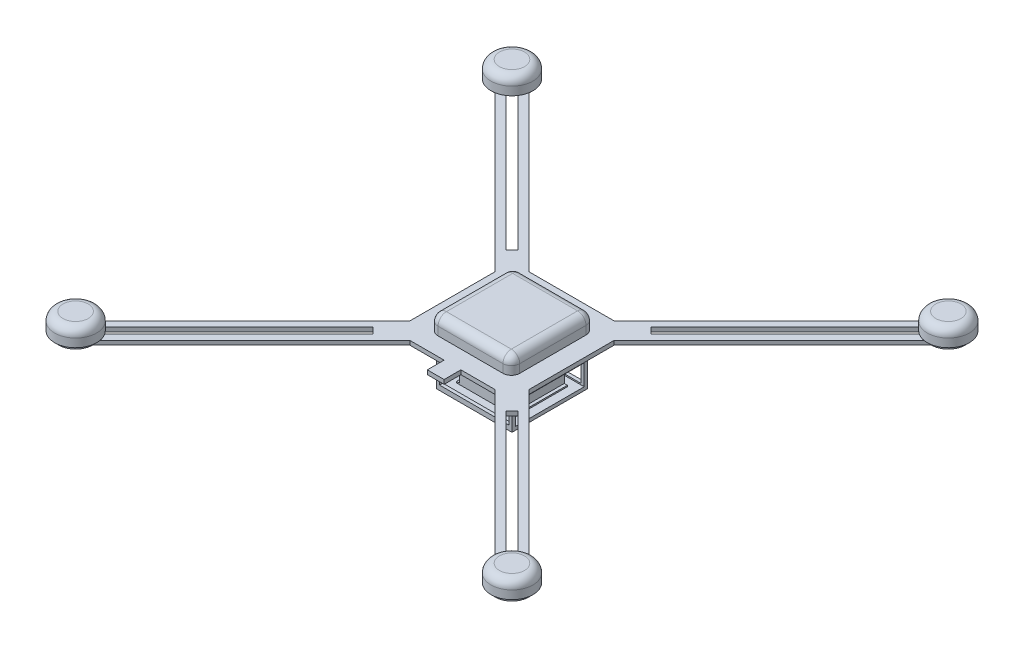
SolidWorks part; units mm, degrees
material "Thornel Mat VMA"
ref_plane "前视" through (0, 0, 0) normal (0, 0, 1) x (1, 0, 0)
ref_plane "上视" through (0, 0, 0) normal (0, 1, 0) x (1, 0, 0)
ref_plane "右视" through (0, 0, 0) normal (1, 0, 0) x (0, 0, -1)
sketch "草图1" plane through (0, 0, 0) normal (0, 1, 0) x (1, 0, 0)
  line L0 (0, 0) -> (260, 0)
  line L1 (260, 0) -> (260, 260)
  line L2 (260, 260) -> (0, 260)
  line L3 (0, 260) -> (0, 0)
  line L4 (0, 70.9035) -> (70.9035, 70.9035)
  line L5 (70.9035, 70.9035) -> (70.9035, 0)
  line L6 (63.5466, 70.9035) -> (252.6432, 260)
  line L7 (70.9035, 63.5466) -> (260, 252.6432)
  line L8 (50.8967, 70.9035) -> (239.9932, 260)
  line L9 (70.9035, 50.8967) -> (260, 239.9932)
  line L10 (72.9627, 92.9694) -> (92.9694, 72.9627)
  circle A0 centre (260, 260) radius 20.0068
extrude "凸台-拉伸1" add sketch "草图1" along normal blind 5 contours L5 L4 L3 L0 | L10 L8 L4 L6 | L10 L6 L4 L5 L7 | L10 L7 L5 L9 | A0 L8 L10 L6 | A0 L7 L10 L9 | L1 A0 L2 | L2 A0 L6 | L7 A0 L1
mirror "镜向1" about plane through (0, 5, 0) normal (1, 0, 0) of "凸台-拉伸1"
mirror "镜向3" about plane through (0, 5, 0) normal (0, 0, -1) of bodies 102
sketch "草图2" plane through (0, 0, 0) normal (0, -1, 0) x (1, 0, 0)
  line L1 (-45, -45) -> (45, -45)
  line L2 (-45, -45) -> (-45, 45)
  line L3 (-45, 45) -> (45, 45)
  line L4 (45, -45) -> (45, 45)
  line L5 (-45, -45) -> (45, 45) construction
  line L6 (-45, 45) -> (45, -45) construction
  point P0 (0, 0)
extrude "凸台-拉伸2" add sketch "草图2" along normal blind 25
sketch "草图3" plane through (0, 0, 45) normal (0, 0, 1) x (1, 0, 0)
  line L1 (-41.3339, -4.7178) -> (41.3339, -4.7178)
  line L2 (-41.3339, -4.7178) -> (-41.3339, -19.776)
  line L3 (-41.3339, -19.776) -> (41.3339, -19.776)
  line L4 (41.3339, -4.7178) -> (41.3339, -19.776)
  line L5 (-41.3339, -4.7178) -> (41.3339, -19.776) construction
  line L6 (-41.3339, -19.776) -> (41.3339, -4.7178) construction
  point P0 (0, -12.2469)
extrude "切除-拉伸1" cut sketch "草图3" against normal blind 90
sketch "草图4" plane through (45, 0, 0) normal (1, 0, 0) x (0, 0, -1)
  line L1 (-41.0428, -3.7748) -> (41.0428, -3.7748)
  line L2 (-41.0428, -3.7748) -> (-41.0428, -20.7699)
  line L3 (-41.0428, -20.7699) -> (41.0428, -20.7699)
  line L4 (41.0428, -3.7748) -> (41.0428, -20.7699)
  line L5 (-41.0428, -3.7748) -> (41.0428, -20.7699) construction
  line L6 (-41.0428, -20.7699) -> (41.0428, -3.7748) construction
  point P0 (0, -12.2724)
extrude "切除-拉伸2" cut sketch "草图4" against normal blind 90
sketch "草图5" plane through (0, 5, 0) normal (0, 1, 0) x (1, 0, 0)
  line L1 (-48.6824, 49.4718) -> (48.6824, 49.4718)
  line L2 (-48.6824, 49.4718) -> (-48.6824, -49.4718)
  line L3 (-48.6824, -49.4718) -> (48.6824, -49.4718)
  line L4 (48.6824, 49.4718) -> (48.6824, -49.4718)
  line L5 (-48.6824, 49.4718) -> (48.6824, -49.4718) construction
  line L6 (-48.6824, -49.4718) -> (48.6824, 49.4718) construction
  point P0 (0, 0)
extrude "凸台-拉伸3" add sketch "草图5" along normal blind 20
fillet "圆角1" radius 10 8 edges at (-48.6824, 15, -49.4718) (48.6824, 15, -49.4718) (48.6824, 15, 49.4718) (48.6824, 25, 0) (0, 25, -49.4718) (-48.6824, 15, 49.4718) (0, 25, 49.4718) (-48.6824, 25, 0)
sketch "草图6" plane through (0, -25, 0) normal (0, -1, 0) x (1, 0, 0)
  line L1 (-45, 45) -> (45, 45)
  line L2 (-45, 45) -> (-45, -45)
  line L3 (-45, -45) -> (45, -45)
  line L4 (45, 45) -> (45, -45)
extrude "凸台-拉伸4" add sketch "草图6" along normal blind 30
sketch "草图7" plane through (0, 0, 45) normal (0, 0, 1) x (1, 0, 0)
  line L0 (-41.3339, -25.4149) -> (41.3339, -25.4149)
  line L1 (41.3339, -25.4149) -> (41.3339, -49.3476)
  line L2 (41.3339, -49.3476) -> (31.3339, -49.3476)
  line L3 (-41.3339, -25.4149) -> (-41.3339, -49.3476)
  line L4 (-41.3339, -49.3476) -> (-31.3339, -49.3476)
  line L5 (-31.3339, -49.3476) -> (-31.3339, -36.2232)
  line L6 (-31.3339, -36.2232) -> (31.3339, -36.2232)
  line L7 (31.3339, -36.2232) -> (31.3339, -49.3476)
extrude "切除-拉伸3" cut sketch "草图7" against normal blind 90
sketch "草图8" plane through (0, 0, 45) normal (0, 0, 1) x (1, 0, 0)
  line L1 (-31.3339, -36.2232) -> (31.3339, -36.2232)
  line L2 (-31.3339, -36.2232) -> (-31.3339, -49.3476)
  line L3 (-31.3339, -49.3476) -> (31.3339, -49.3476)
  line L4 (31.3339, -36.2232) -> (31.3339, -49.3476)
extrude "切除-拉伸4" cut sketch "草图8" against normal blind 10
sketch "草图9" plane through (45, 0, 0) normal (1, 0, 0) x (0, 0, -1)
  line L0 (-41.0428, -26.2736) -> (-41.0428, -50.9435)
  line L1 (-41.0428, -26.2736) -> (41.0428, -26.2736)
  line L2 (41.0428, -26.2736) -> (41.0428, -50.9435)
  line L3 (41.0428, -50.9435) -> (31.0428, -50.9435)
  line L4 (-41.0428, -50.9435) -> (-31.0428, -50.9435)
  line L5 (-31.0428, -50.9435) -> (-31.0428, -29.3173)
  line L6 (-31.0428, -29.3173) -> (31.0428, -29.3173)
  line L7 (31.0428, -29.3173) -> (31.0428, -50.9435)
extrude "切除-拉伸5" cut sketch "草图9" against normal blind 90
sketch "草图10" plane through (45, 0, 0) normal (1, 0, 0) x (0, 0, -1)
  line L1 (-31.0428, -29.3173) -> (31.0428, -29.3173)
  line L2 (-31.0428, -29.3173) -> (-31.0428, -50.9435)
  line L3 (-31.0428, -50.9435) -> (31.0428, -50.9435)
  line L4 (31.0428, -29.3173) -> (31.0428, -50.9435)
extrude "切除-拉伸6" cut sketch "草图10" against normal blind 10
sketch "草图11" plane through (0, 0, -45) normal (0, 0, -1) x (-1, 0, 0)
  line L1 (-31.3339, -36.2232) -> (31.3339, -36.2232)
  line L2 (-31.3339, -36.2232) -> (-31.3339, -49.3476)
  line L3 (-31.3339, -49.3476) -> (31.3339, -49.3476)
  line L4 (31.3339, -36.2232) -> (31.3339, -49.3476)
extrude "切除-拉伸7" cut sketch "草图11" against normal blind 10
sketch "草图12" plane through (-45, 0, 0) normal (-1, 0, 0) x (0, 0, 1)
  line L1 (-31.0428, -29.3173) -> (31.0428, -29.3173)
  line L2 (-31.0428, -29.3173) -> (-31.0428, -50.9435)
  line L3 (-31.0428, -50.9435) -> (31.0428, -50.9435)
  line L4 (31.0428, -29.3173) -> (31.0428, -50.9435)
extrude "切除-拉伸8" cut sketch "草图12" against normal blind 10
sketch "草图13" plane through (0, 0, 70.9035) normal (0, 0, 1) x (1, 0, 0)
  line L0 (0, 0) -> (-10, 0)
  line L1 (-50.8967, 0) -> (50.8967, 0) construction
  line L2 (0, 0) -> (10, 0)
  line L3 (45, 0) -> (-45, 0) construction
  line L4 (10, 0) -> (10, 5)
  line L5 (-38.6824, 5) -> (38.6824, 5) construction
  line L6 (10, 5) -> (-10, 5)
  line L7 (-10, 5) -> (-10, 0)
extrude "凸台-拉伸5" add sketch "草图13" along normal blind 20
sketch "草图14" plane through (0, 5, 0) normal (0, 1, 0) x (1, 0, 0)
  circle A0 centre (-260, 260) radius 25
  circle A1 centre (260, 260) radius 25
  circle A2 centre (-260, -260) radius 25
  circle A3 centre (260, -260) radius 25
extrude "凸台-拉伸6" add sketch "草图14" along normal blind 20
fillet "圆角2" radius 10 4 edges at (260, 25, 285) (260, 25, -235) (-260, 25, -235) (-260, 25, 285)
scale "缩放比例1" scale about centroid uniform scaling yes scale factor 0.5
sketch3d "URDF Reference"
  line L0 (0, 0, 0) -> (10, 0, 0) construction
  line L1 (0, 0, 0) -> (0, 0, -10) construction
  point P0 (0, 0, 0)
  point P1 (0, 0, 0)
